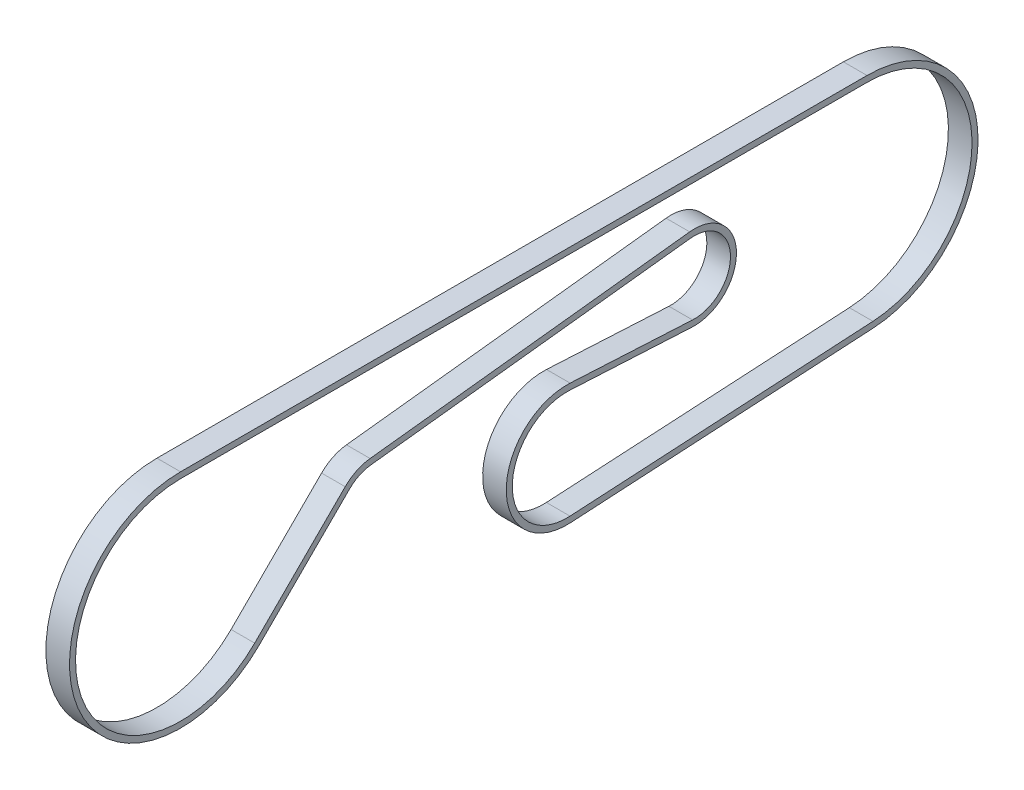
SolidWorks part; units mm, degrees
material "BUTYL"
ref_plane "Front Plane" through (0, 0, 0) normal (1, 0, 0) x (0, 1, 0)
ref_plane "Top Plane" through (0, 0, 0) normal (0, 0, 1) x (0, 1, 0)
ref_plane "Right Plane" through (0, 0, 0) normal (0, 1, 0) x (-1, 0, 0)
sketch "Sketch1" plane through (0, 0, 0) normal (1, 0, 0) x (0, 1, 0)
  line L0 (-81.8446, -48.4473) -> (-84.7583, 2.8366)
  line L1 (-66.2862, 2.8714) -> (-67.3852, -17.8521)
  line L2 (-53.2171, -17.4224) -> (-59.3906, 36.6796)
  line L3 (-61.4189, 40.8933) -> (-76.6877, 56.2161)
  line L4 (-46.3132, 68.7663) -> (-46.3132, -47.4387)
  line L5 (-45.2972, 68.7663) -> (-45.2972, -47.4387)
  line L6 (-82.8589, -48.5049) -> (-85.7727, 2.7789)
  line L7 (-65.2716, 2.8176) -> (-66.3707, -17.9059)
  line L8 (-54.2265, -17.5376) -> (-60.4, 36.5644)
  line L9 (-62.1386, 40.1762) -> (-77.4074, 55.499)
  arc A0 (-81.8446, -48.4473) -> (-46.3132, -47.4387) centre (-64.0932, -47.4387) ccw
  arc A1 (-67.3852, -17.8521) -> (-53.2171, -17.4224) centre (-60.2832, -18.2287) ccw
  arc A2 (-84.7583, 2.8366) -> (-66.2862, 2.8714) centre (-75.5232, 3.3613) cw
  arc A3 (-59.3906, 36.6796) -> (-61.4189, 40.8933) centre (-66.4567, 35.8733) ccw
  arc A4 (-76.6877, 56.2161) -> (-46.3132, 68.7663) centre (-64.0932, 68.7663) cw
  arc A5 (-77.4074, 55.499) -> (-45.2972, 68.7663) centre (-64.0932, 68.7663) cw
  arc A6 (-82.8589, -48.5049) -> (-45.2972, -47.4387) centre (-64.0932, -47.4387) ccw
  arc A7 (-85.7727, 2.7789) -> (-65.2716, 2.8176) centre (-75.5232, 3.3613) cw
  arc A8 (-66.3707, -17.9059) -> (-54.2265, -17.5376) centre (-60.2832, -18.2287) ccw
  arc A9 (-60.4, 36.5644) -> (-62.1386, 40.1762) centre (-66.4567, 35.8733) ccw
extrude "Boss-Extrude1" add sketch "Sketch1" along normal blind 4
